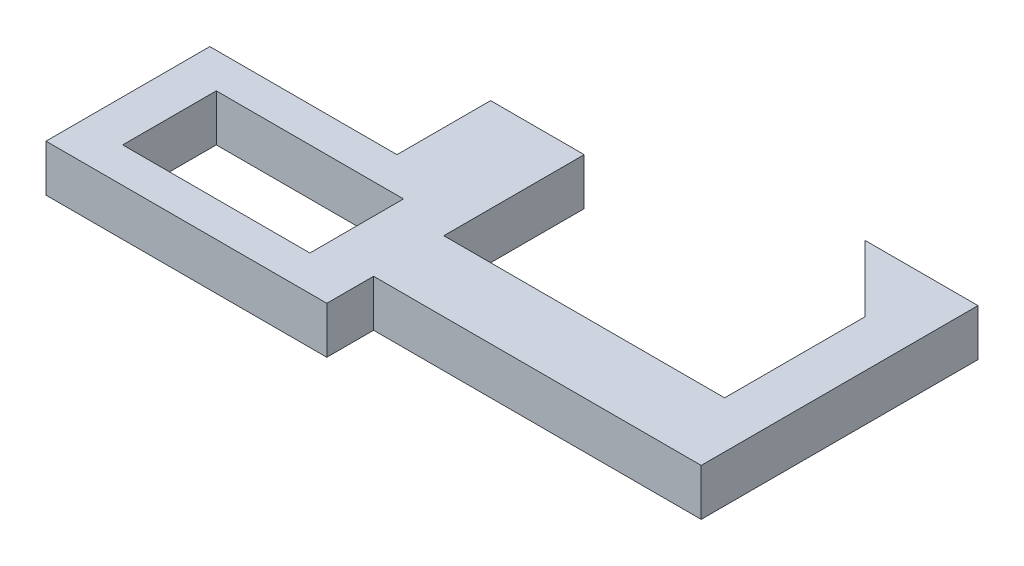
SolidWorks part; units mm, degrees
ref_plane "Front Plane" through (0, 0, 0) normal (0, 0, 1) x (1, 0, 0)
ref_plane "Top Plane" through (0, 0, 0) normal (0, 1, 0) x (1, 0, 0)
ref_plane "Right Plane" through (0, 0, 0) normal (1, 0, 0) x (0, 0, -1)
sketch "Sketch1" plane through (0, 0, 0) normal (0, 1, 0) x (1, 0, 0)
  line L0 (-27.9733, 22.1922) -> (-24.9733, 22.1922)
  line L1 (-24.9733, 22.1922) -> (-24.9733, 23.6922)
  line L2 (-24.9733, 23.6922) -> (-25.6804, 24.3993)
  line L3 (-25.6804, 24.3993) -> (-24.4733, 24.3993)
  line L4 (-24.4733, 24.3993) -> (-24.4733, 21.4422)
  line L5 (-27.9733, 22.1922) -> (-27.9733, 21.4422)
  line L6 (-27.9733, 21.4422) -> (-24.4733, 21.4422)
  line L7 (-27.9733, 22.1922) -> (-27.9733, 22.6922)
  line L8 (-27.9733, 22.6922) -> (-30.9733, 22.6922)
  line L9 (-27.9733, 21.4422) -> (-27.9733, 20.9422)
  line L10 (-27.9733, 20.9422) -> (-30.9733, 20.9422)
  line L11 (-30.9733, 20.9422) -> (-30.9733, 22.6922)
  line L12 (-27.9733, 22.6922) -> (-27.9733, 23.6922)
  line L13 (-27.9733, 23.6922) -> (-28.9733, 23.6922)
  line L14 (-30.9733, 21.8172) -> (-29.5288, 21.8172)
  line L15 (-28.9733, 23.6922) -> (-28.9733, 22.6922)
  line L16 (-29.5288, 21.8172) -> (-29.5288, 22.3172)
  line L17 (-29.5288, 22.3172) -> (-28.5288, 22.3172)
  line L18 (-28.5288, 22.3172) -> (-28.5288, 21.3172)
  line L19 (-28.5288, 21.3172) -> (-30.5288, 21.3172)
  line L20 (-30.5288, 21.3172) -> (-30.5288, 22.3172)
  line L21 (-30.5288, 22.3172) -> (-29.5288, 22.3172)
extrude "Boss-Extrude1" add sketch "Sketch1" along normal blind 0.5 contours L11 L10 L9 L5 L7 L8 | L5 L6 L4 L3 L2 L1 L0 | L13 L15 L8 L12
